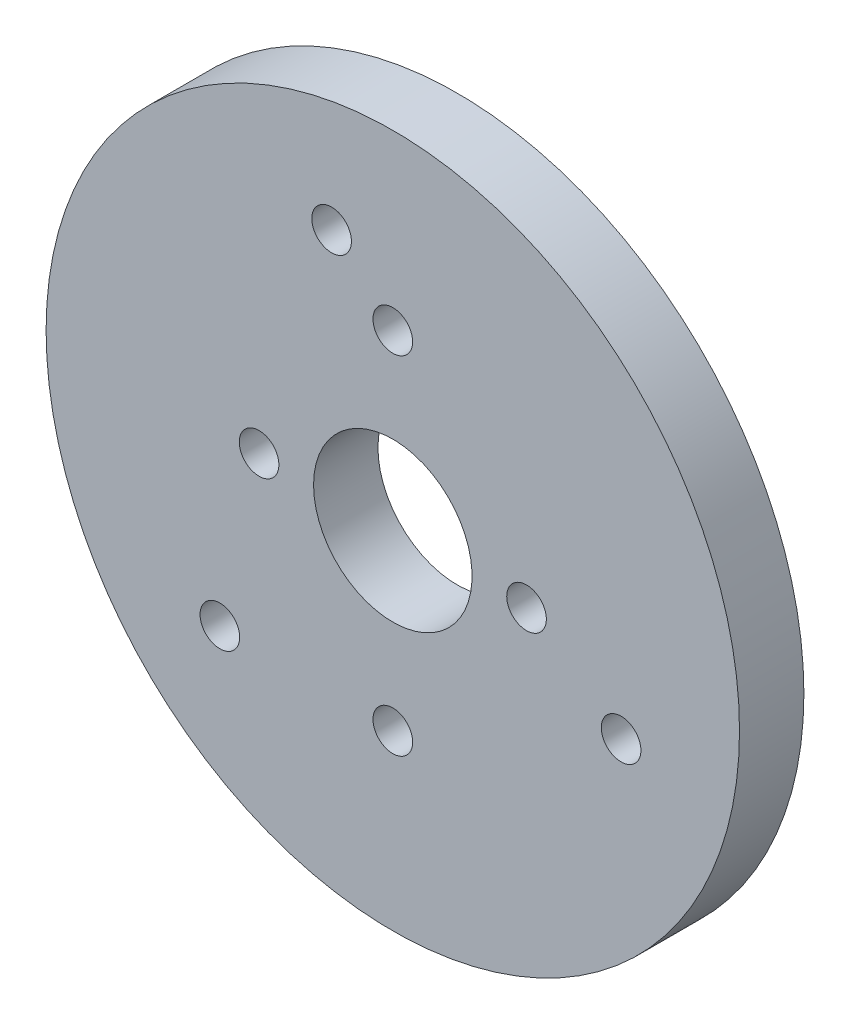
SolidWorks part; units mm, degrees
material "1060 Alloy"
ref_plane "Front" through (0, 0, 0) normal (0, 0, 1) x (1, 0, 0)
ref_plane "Top" through (0, 0, 0) normal (0, 1, 0) x (1, 0, 0)
ref_plane "Right" through (0, 0, 0) normal (1, 0, 0) x (0, 0, -1)
sketch "Sketch1" plane through (0, 0, 0) normal (0, 0, 1) x (1, 0, 0)
  line L0 (6.75, 0) -> (0, 0) construction
  line L1 (0, 0) -> (0, 8.75) construction
  circle A0 centre (0, 0) radius 17.5
  circle A1 centre (0, 0) radius 4
  circle A2 centre (6.75, 0) radius 1
  circle A3 centre (0, 8.75) radius 1
  circle A4 centre (0, -8.75) radius 1
  circle A5 centre (-6.75, 0) radius 1
  dimension "D1" = 35
  dimension "D2" = 8
  dimension "D4" = 2
  dimension "D3" = 6.75
  dimension "D5" = 8.75
extrude "Boss-Extrude1" add sketch "Sketch1" along normal blind 3.25
sketch "Sketch2" plane through (0, 0, 3.25) normal (0, 0, 1) x (1, 0, 0)
  circle A0 centre (-3.0891, 11.598) radius 1 construction
  circle A3 centre (11.5227, -3.3506) radius 1 construction
  circle A4 centre (-8.729, -8.5305) radius 1 construction
  circle A5 centre (11.5227, -3.3506) radius 1
  circle A6 centre (-8.729, -8.5305) radius 1
  circle A7 centre (-3.0891, 11.598) radius 1
extrude "Cut-Extrude1" cut sketch "Sketch2" against normal through all
